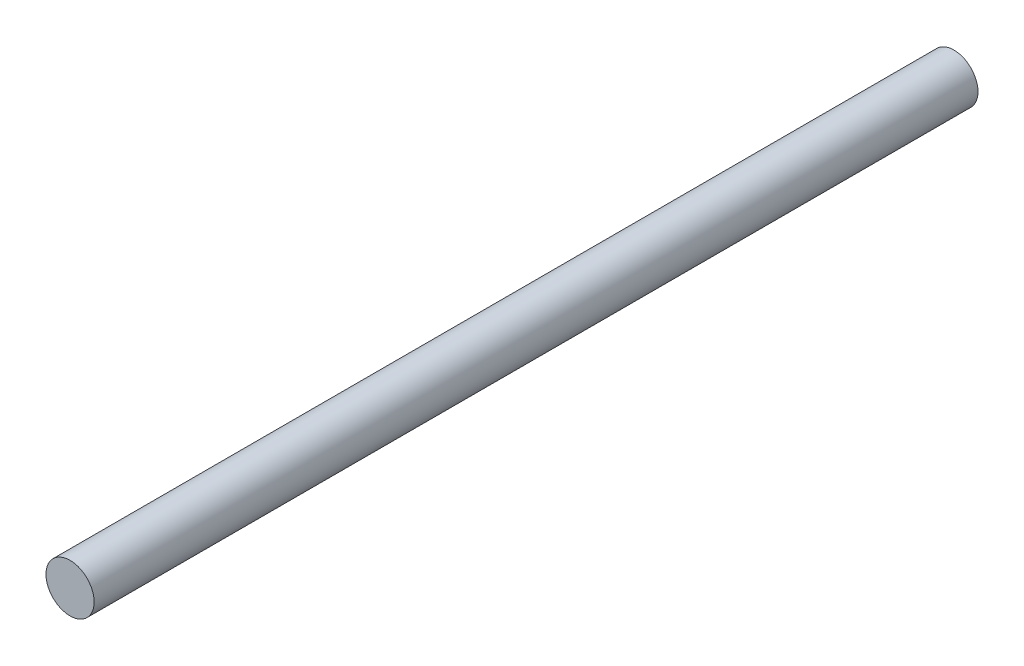
SolidWorks part; units mm, degrees
material "Plain Carbon Steel"
ref_plane "Front Plane" through (0, 0, 0) normal (0, 0, 1) x (1, 0, 0)
ref_plane "Top Plane" through (0, 0, 0) normal (0, 1, 0) x (1, 0, 0)
ref_plane "Right Plane" through (0, 0, 0) normal (1, 0, 0) x (0, 0, -1)
sketch "Sketch1" plane through (0, 0, 0) normal (0, 0, 1) x (1, 0, 0)
  circle A0 centre (0, 0) radius 1.3843
  dimension "D1" = 2.7686
extrude "Boss-Extrude1" add sketch "Sketch1" along normal blind 50.8
